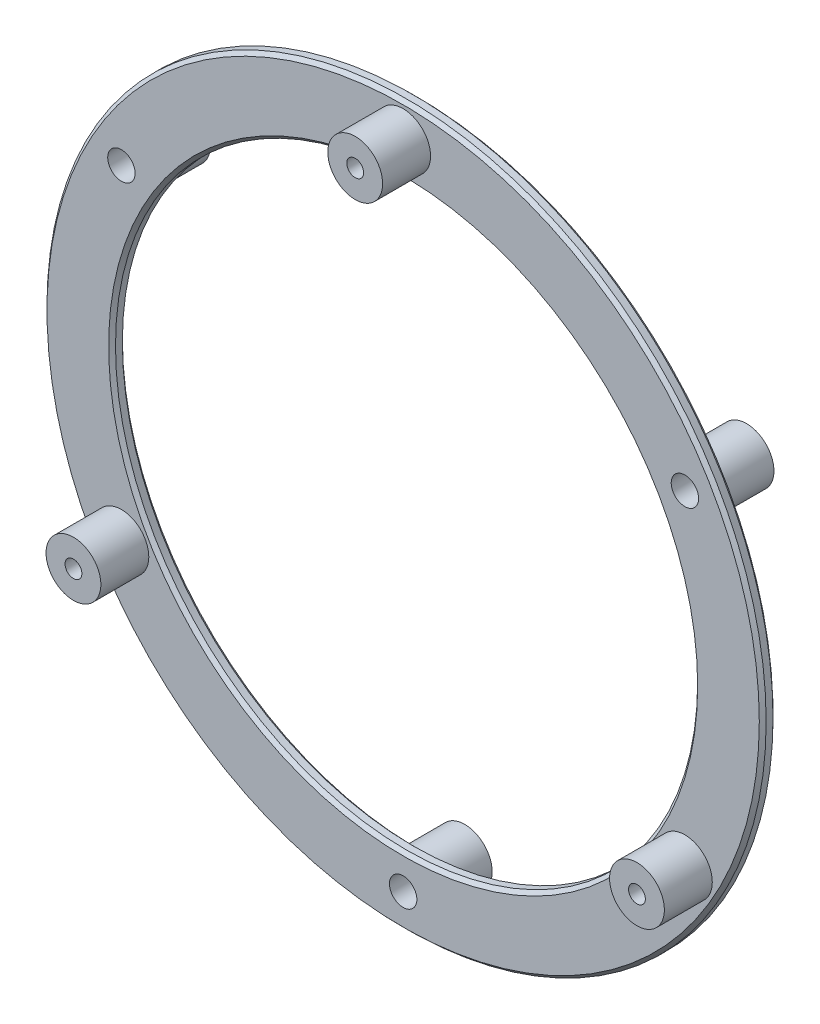
SolidWorks part; units mm, degrees
ref_plane "Front Plane" through (0, 0, 0) normal (0, 0, 1) x (1, 0, 0)
ref_plane "Top Plane" through (0, 0, 0) normal (0, 1, 0) x (1, 0, 0)
ref_plane "Right Plane" through (0, 0, 0) normal (1, 0, 0) x (0, 0, -1)
ref_plane "Plane1" through (0, 0, 0) normal (0, -1, 0) x (1, 0, 0)
sketch "Sketch1" plane through (0, 0, 0) normal (0, -1, 0) x (1, 0, 0)
  line L0 (52.5, 2) -> (0, 2)
  line L1 (0, 2) -> (0, 0)
  line L2 (0, 0) -> (52.5, 0)
  line L3 (52.5, 0) -> (52.5, 2)
  line L4 (0, 2) -> (0, 0) construction
revolve "Revolve1" add sketch "Sketch1" angle 360 about L4
ref_plane "Plane2" through (0, -23.75, 0) normal (0, -1, 0) x (1, 0, 0)
sketch "Sketch2" plane through (0, -23.75, 0) normal (0, -1, 0) x (1, 0, 0)
  line L0 (45.1362, 9) -> (41.1362, 9)
  line L1 (41.1362, 9) -> (41.1362, 2)
  line L2 (41.1362, 2) -> (45.1362, 2)
  line L3 (45.1362, 2) -> (45.1362, 9)
  line L4 (41.1362, 9) -> (41.1362, 2) construction
revolve "Revolve2" add sketch "Sketch2" angle 360 about L4
sketch "Sketch3" plane through (0, -23.75, 0) normal (0, -1, 0) x (1, 0, 0)
  line L0 (-37.1362, 9) -> (-41.1362, 9)
  line L1 (-41.1362, 9) -> (-41.1362, 2)
  line L2 (-41.1362, 2) -> (-37.1362, 2)
  line L3 (-37.1362, 2) -> (-37.1362, 9)
  line L4 (-41.1362, 9) -> (-41.1362, 2) construction
revolve "Revolve3" add sketch "Sketch3" angle 360 about L4
ref_plane "Plane3" through (0, 47.5, 0) normal (0, -1, 0) x (1, 0, 0)
sketch "Sketch4" plane through (0, 47.5, 0) normal (0, -1, 0) x (1, 0, 0)
  line L0 (4, 9) -> (0, 9)
  line L1 (0, 9) -> (0, 2)
  line L2 (0, 2) -> (4, 2)
  line L3 (4, 2) -> (4, 9)
  line L4 (0, 9) -> (0, 2) construction
revolve "Revolve4" add sketch "Sketch4" angle 360 about L4
ref_plane "Plane4" through (0, 23.75, 0) normal (0, 1, 0) x (1, 0, 0)
sketch "Sketch5" plane through (0, 23.75, 0) normal (0, 1, 0) x (1, 0, 0)
  line L0 (45.1362, 7) -> (41.1362, 7)
  line L1 (41.1362, 7) -> (41.1362, 0)
  line L2 (41.1362, 0) -> (45.1362, 0)
  line L3 (45.1362, 0) -> (45.1362, 7)
  line L4 (41.1362, 7) -> (41.1362, 0) construction
revolve "Revolve5" add sketch "Sketch5" angle 360 about L4
sketch "Sketch6" plane through (0, 23.75, 0) normal (0, 1, 0) x (1, 0, 0)
  line L0 (-37.1362, 7) -> (-41.1362, 7)
  line L1 (-41.1362, 7) -> (-41.1362, 0)
  line L2 (-41.1362, 0) -> (-37.1362, 0)
  line L3 (-37.1362, 0) -> (-37.1362, 7)
  line L4 (-41.1362, 7) -> (-41.1362, 0) construction
revolve "Revolve6" add sketch "Sketch6" angle 360 about L4
ref_plane "Plane5" through (0, -47.5, 0) normal (0, 1, 0) x (1, 0, 0)
sketch "Sketch7" plane through (0, -47.5, 0) normal (0, 1, 0) x (1, 0, 0)
  line L0 (4, 7) -> (0, 7)
  line L1 (0, 7) -> (0, 0)
  line L2 (0, 0) -> (4, 0)
  line L3 (4, 0) -> (4, 7)
  line L4 (0, 7) -> (0, 0) construction
revolve "Revolve7" add sketch "Sketch7" angle 360 about L4
ref_plane "Plane6" through (0, 47.5, 0) normal (0, 1, 0) x (1, 0, 0)
sketch "Sketch8" plane through (0, 47.5, 0) normal (0, 1, 0) x (1, 0, 0)
  line L0 (1.2295, 0) -> (0, 0)
  line L1 (0, 0) -> (0, -9)
  line L2 (0, -9) -> (1.2295, -9)
  line L3 (1.2295, -9) -> (1.2295, -7)
  line L4 (1.2295, -7) -> (1.2295, 0)
  line L5 (0, 0) -> (0, -9) construction
revolve "Cut-Revolve1" cut sketch "Sketch8" angle 360 about L5
ref_plane "Plane7" through (0, -23.75, 0) normal (0, 1, 0) x (1, 0, 0)
sketch "Sketch9" plane through (0, -23.75, 0) normal (0, 1, 0) x (1, 0, 0)
  line L0 (-39.9067, 0) -> (-41.1362, 0)
  line L1 (-41.1362, 0) -> (-41.1362, -9)
  line L2 (-41.1362, -9) -> (-39.9067, -9)
  line L3 (-39.9067, -9) -> (-39.9067, -7)
  line L4 (-39.9067, -7) -> (-39.9067, 0)
  line L5 (-41.1362, 0) -> (-41.1362, -9) construction
revolve "Cut-Revolve2" cut sketch "Sketch9" angle 360 about L5
sketch "Sketch10" plane through (0, -23.75, 0) normal (0, 1, 0) x (1, 0, 0)
  line L0 (42.3657, 0) -> (41.1362, 0)
  line L1 (41.1362, 0) -> (41.1362, -9)
  line L2 (41.1362, -9) -> (42.3657, -9)
  line L3 (42.3657, -9) -> (42.3657, -7)
  line L4 (42.3657, -7) -> (42.3657, 0)
  line L5 (41.1362, 0) -> (41.1362, -9) construction
revolve "Cut-Revolve3" cut sketch "Sketch10" angle 360 about L5
hole_wizard "Ø4.0 (4) Diameter Hole1" positions "Sketch12" profile "Sketch11" hole size "Ø4.0" standard "ANSI Metric" end condition through all
sketch "Sketch12" plane through (0, 0, -7) normal (0, 0, -1) x (-1, 0, 0)
  point P0 (-41.1362, 23.75)
  point P1 (0, -47.5)
  point P2 (41.1362, 23.75)
sketch "Sketch11" plane through (41.1362, 23.75, -7) normal (1, 0, 0) x (0, 1, 0)
  line L0 (0, 0) -> (0, 16)
  line L1 (0, 16) -> (2, 16)
  line L2 (2, 16) -> (2, 0)
  line L5 (2, 0) -> (0, 0)
  line L11 (0, -6.35) -> (0, 107.95) construction
  dimension "Thru Hole Dia." = 4
  dimension "Thru Hole Depth" = 16
hole_wizard "M80 Clearance Hole1" positions "Sketch14" profile "Sketch13" hole size "M80" standard "ANSI Metric"
sketch "Sketch14" plane through (0, 0, 2) normal (0, 0, 1) x (1, 0, 0)
  point P0 (0, 0)
sketch "Sketch13" plane through (0, 0, 2) normal (1, 0, 0) x (0, -1, 0)
  line L0 (0, 0) -> (0, 9)
  line L1 (0, 9) -> (42.5, 9)
  line L2 (42.5, 9) -> (42.5, 0)
  line L5 (42.5, 0) -> (0, 0)
  line L11 (0, -6.35) -> (0, 107.95) construction
  dimension "Thru Hole Dia." = 85
  dimension "Thru Hole Depth" = 9
chamfer "Chamfer1" distance 0.5 angle 45 4 edges at (-52.5, 0, 0) (-52.5, 0, 2) (-42.5, 0, 0) (42.5, 0, 2)
